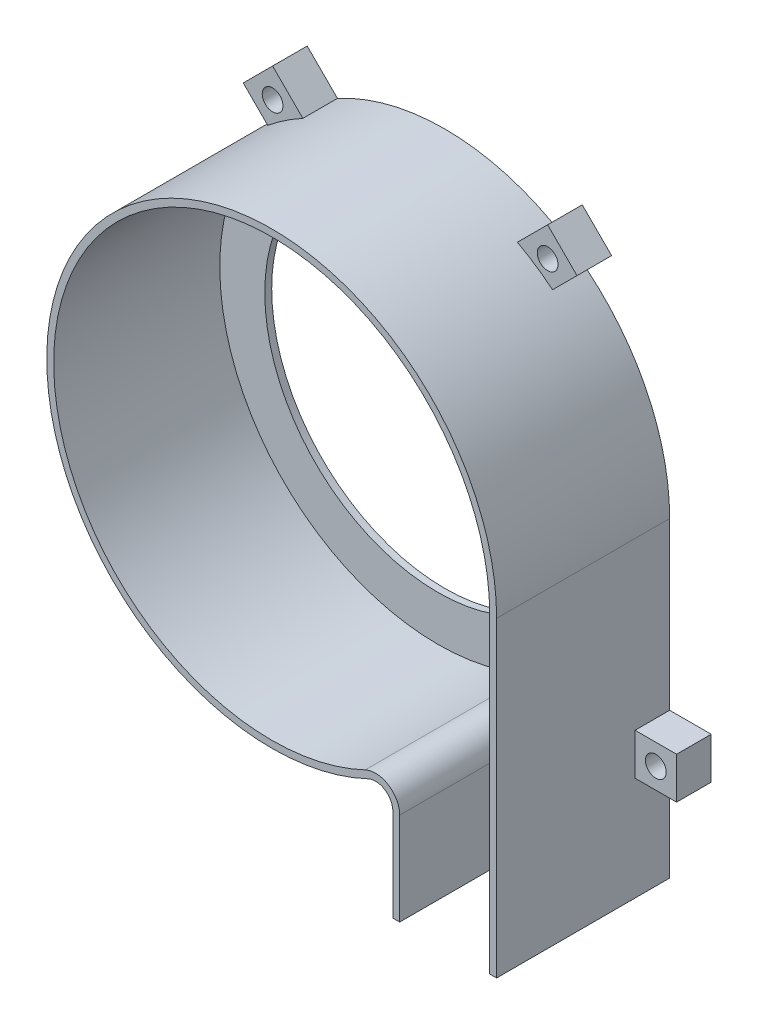
SolidWorks part; units mm, degrees
ref_plane "Plan de face" through (0, 0, 0) normal (0, 0, 1) x (1, 0, 0)
ref_plane "Plan de dessus" through (0, 0, 0) normal (0, 1, 0) x (1, 0, 0)
ref_plane "Plan de droite" through (0, 0, 0) normal (1, 0, 0) x (0, 0, -1)
sketch "Esquisse1" plane through (0, 0, 0) normal (0, 0, 1) x (1, 0, 0)
  line L0 (32.5, 0) -> (32.5, -45)
  line L1 (17.5, -31.6228) -> (17.5, -45)
  line L2 (17.5, -45) -> (32.5, -45)
  arc A0 (32.5, 0) -> (13.9286, -29.364) centre (0, 0) ccw
  arc A1 (17.5, -31.6228) -> (13.9286, -29.364) centre (15, -31.6228) ccw
  circle A2 centre (0, 0) radius 25
  dimension "D1" = 65
  dimension "D4" = 5
  dimension "D5" = 50
  dimension "D2" = 45
  dimension "D3" = 15
extrude "Boss.-Extru.1" add sketch "Esquisse1" along normal blind 30
shell "Coque1" thickness 1
sketch "Esquisse2" plane through (0, 0, 30) normal (0, 0, 1) x (1, 0, 0)
  line L3 (17.5, -31.6228) -> (17.5, -45)
  line L4 (17.5, -45) -> (32.5, -45)
  line L5 (32.5, -45) -> (32.5, 0)
  line L6 (17.5, -31.6228) -> (17.5, -45)
  line L7 (17.5, -45) -> (32.5, -45)
  line L8 (32.5, -45) -> (32.5, 0)
  arc A2 (32.5, 0) -> (13.9286, -29.364) centre (0, 0) ccw
  arc A3 (17.5, -31.6228) -> (13.9286, -29.364) centre (15, -31.6228) ccw
  arc A4 (32.5, 0) -> (13.9286, -29.364) centre (0, 0) ccw
  arc A5 (17.5, -31.6228) -> (13.9286, -29.364) centre (15, -31.6228) ccw
  dimension "D1" = 0
extrude "Enlèv. mat.-Extru.1" cut sketch "Esquisse2" against normal blind 5
sketch "Esquisse4" plane through (0, 0, 0) normal (0, 0, -1) x (-1, 0, 0)
  line L0 (-20.5766, 25.1566) -> (-24.1121, 28.6921)
  line L1 (0, 12.0536) -> (0, 38.9566) construction
  line L2 (-24.1121, 28.6921) -> (-19.8695, 32.9348)
  line L3 (-19.8695, 32.9348) -> (-15.5003, 28.5656)
  line L4 (19.8695, 32.9348) -> (15.5003, 28.5656)
  line L5 (24.1121, 28.6921) -> (19.8695, 32.9348)
  line L6 (20.5766, 25.1566) -> (24.1121, 28.6921)
  line L7 (-32.5, -45) -> (-32.5, 0) construction
  line L8 (-32.5, -30) -> (-32.5, -24)
  line L9 (-32.5, -30) -> (-38.5, -30)
  line L10 (-38.5, -30) -> (-38.5, -24)
  line L11 (-38.5, -24) -> (-32.5, -24)
  line L12 (-17.5, -45) -> (-32.5, -45) construction
  arc A0 (-13.9286, -29.364) -> (-32.5, 0) centre (0, 0) ccw construction
  arc A1 (-13.9286, -29.364) -> (-32.5, 0) centre (0, 0) ccw
  circle A2 centre (-19.8695, 28.6921) radius 1.5
  circle A3 centre (19.8695, 28.6921) radius 1.5
  circle A4 centre (-35.5, -27) radius 1.5
  arc M8 (-13.9286, -29.364) -> (-32.5, 0) centre (0, 0) ccw
  line M9 (-32.5, 0) -> (-32.5, -45)
  dimension "D4" = 3
  dimension "D8" = 3
  dimension "D1" = 45
  dimension "D2" = 6
  dimension "D3" = 5
  dimension "D5" = 6
  dimension "D6" = 6
  dimension "D7" = 15
extrude "Boss.-Extru.3" add sketch "Esquisse4" against normal blind 5 contours L11 L10 L9 A4 M9 | L3 L2 L0 A2 M8 | L6 L5 L4 A3 M8
